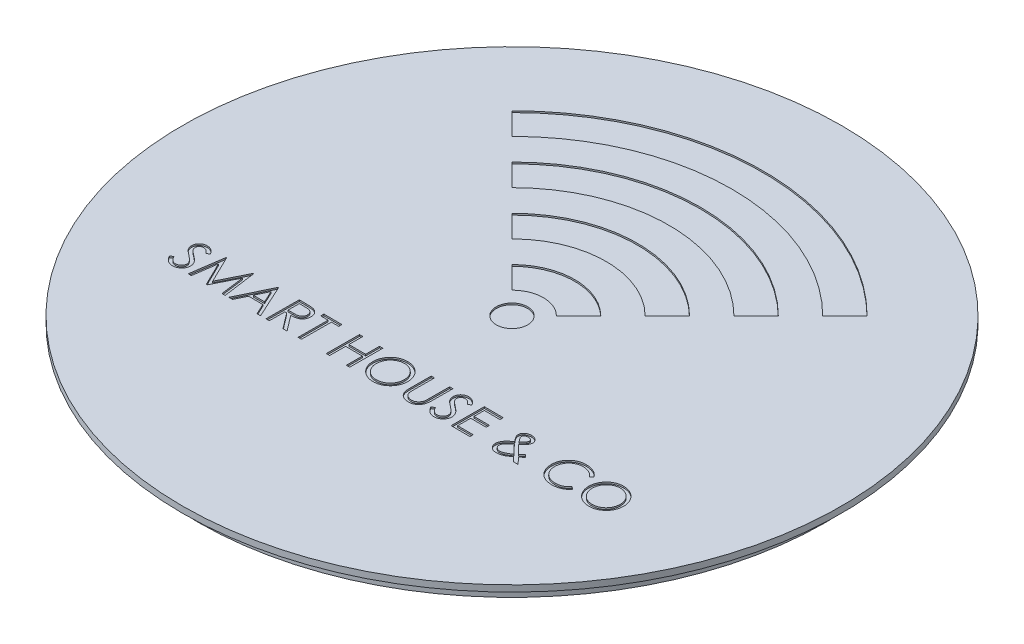
SolidWorks part; units mm, degrees
material "ABS"
ref_plane "Alzado" through (0, 0, 0) normal (0, 0, 1) x (1, 0, 0)
ref_plane "Planta" through (0, 0, 0) normal (0, 1, 0) x (1, 0, 0)
ref_plane "Vista lateral" through (0, 0, 0) normal (1, 0, 0) x (0, 0, -1)
sketch "Croquis1" plane through (0, 0, 0) normal (0, 1, 0) x (1, 0, 0)
  circle A0 centre (0, 0) radius 105
extrude "Saliente-Extruir1" add sketch "Croquis1" along normal blind 2
sketch "Croquis7" plane through (0, 0, 0) normal (0, -1, 0) x (1, 0, 0)
  circle A0 centre (0, 0) radius 100
extrude "Saliente-Extruir4" add sketch "Croquis7" along normal blind 5
sketch "Croquis8" plane through (0, 2, 0) normal (0, 1, 0) x (1, 0, 0)
  line L0 (7.0711, 7.0711) -> (14.1421, 14.1421)
  line L1 (-7.0711, 7.0711) -> (-14.1421, 14.1421)
  line L2 (-21.2132, 21.2132) -> (-28.2843, 28.2843)
  line L3 (21.2132, 21.2132) -> (28.2843, 28.2843)
  line L4 (-35.3553, 35.3553) -> (-42.4264, 42.4264)
  line L5 (-49.4975, 49.4975) -> (-56.5685, 56.5685)
  line L6 (49.4975, 49.4975) -> (56.5685, 56.5685)
  line L7 (35.3553, 35.3553) -> (42.4264, 42.4264)
  line L8 (0, 0) -> (0, -40) construction
  line L9 (75, -40) -> (-75, -40) construction
  arc A0 (35.3553, 35.3553) -> (-35.3553, 35.3553) centre (0, 0) ccw
  arc A1 (28.2843, 28.2843) -> (-28.2843, 28.2843) centre (0, 0) ccw
  arc A2 (21.2132, 21.2132) -> (-21.2132, 21.2132) centre (0, 0) ccw
  arc A3 (14.1421, 14.1421) -> (-14.1421, 14.1421) centre (0, 0) ccw
  arc A4 (7.0711, 7.0711) -> (-7.0711, 7.0711) centre (0, 0) ccw
  arc A5 (42.4264, 42.4264) -> (-42.4264, 42.4264) centre (0, 0) ccw
  arc A6 (49.4975, 49.4975) -> (-49.4975, 49.4975) centre (0, 0) ccw
  arc A7 (56.5685, 56.5685) -> (-56.5685, 56.5685) centre (0, 0) ccw
  circle A8 centre (0, 0) radius 5
  text T0 "SMART HOUSE & CO" font "Century Gothic" height in points 40
  dimension "D1" = 75
  dimension "D2" = 150
extrude "Cortar-Extruir6" cut sketch "Croquis8" against normal blind 0.5
